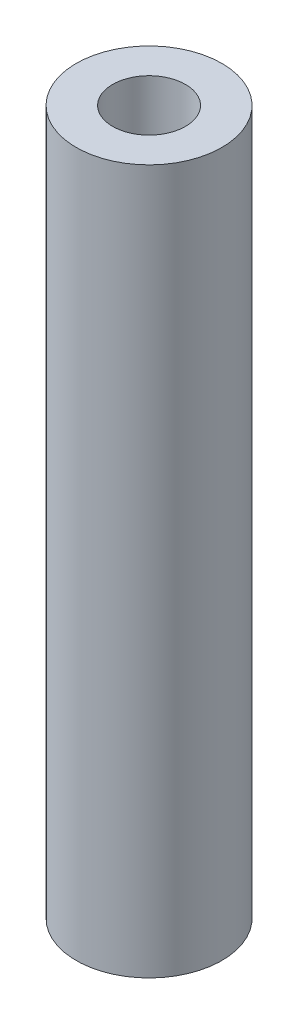
SolidWorks part; units mm, degrees
ref_plane "Front Plane" through (0, 0, 0) normal (0, 0, 1) x (1, 0, 0)
ref_plane "Top Plane" through (0, 0, 0) normal (0, 1, 0) x (1, 0, 0)
ref_plane "Right Plane" through (0, 0, 0) normal (1, 0, 0) x (0, 0, -1)
sketch "Sketch1" plane through (0, 0, 0) normal (0, 1, 0) x (1, 0, 0)
  circle A0 centre (0, 0) radius 1.5
  circle A1 centre (0, 0) radius 3
  dimension "D1" = 6
  dimension "D2" = 3
extrude "standoff" add sketch "Sketch1" along normal blind 29
